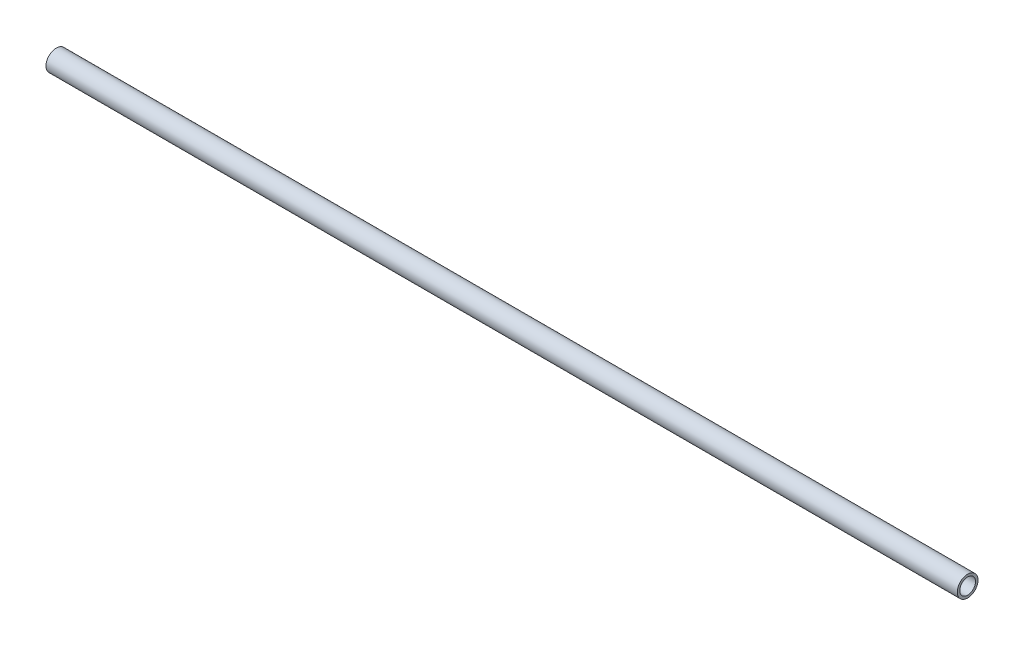
SolidWorks part; units mm, degrees
material "AISI 4130 Steel, annealed at 865C"
ref_plane "Front Plane" through (0, 0, 0) normal (0, 0, 1) x (1, 0, 0)
ref_plane "Top Plane" through (0, 0, 0) normal (0, 1, 0) x (1, 0, 0)
ref_plane "Right Plane" through (0, 0, 0) normal (1, 0, 0) x (0, 0, -1)
sketch "Sketch1" plane through (0, 0, 0) normal (1, 0, 0) x (0, 0, -1)
  circle A0 centre (0, 0) radius 12.7
  circle A1 centre (0, 0) radius 9.652
  dimension "D1" = 25.4
  dimension "D2" = 19.304
extrude "Boss-Extrude1" add sketch "Sketch1" along normal blind 1117.6
